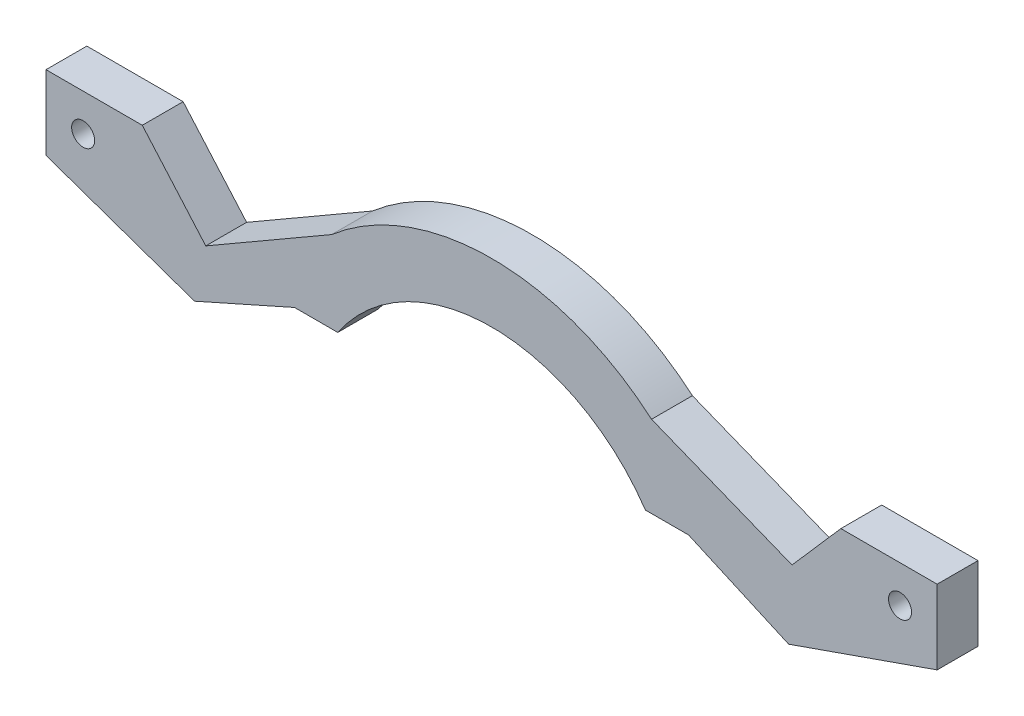
SolidWorks part; units mm, degrees
material "ﾁｰｸ材"
ref_plane "正面" through (0, 0, 0) normal (0, 0, 1) x (1, 0, 0)
ref_plane "平面" through (0, 0, 0) normal (0, 1, 0) x (1, 0, 0)
ref_plane "右側面" through (0, 0, 0) normal (1, 0, 0) x (0, 0, -1)
sketch "ｽｹｯﾁ1" plane through (0, 0, 0) normal (0, 0, 1) x (1, 0, 0)
  line L0 (-60, 5) -> (-47.0333, 5)
  line L2 (60, 5) -> (60, -5)
  line L4 (-60, 5) -> (-60, -5)
  line L5 (60, 5) -> (-60, -5) construction
  line L6 (60, -5) -> (-60, 5) construction
  line L7 (-60, -5) -> (-40, -12)
  line L8 (29.5804, -15) -> (47.0333, 5) construction
  line L9 (-29.5804, -15) -> (-47.0333, 5) construction
  line L10 (-40, -12) -> (-26.533, -6)
  line L11 (-47.0333, 5) -> (-38.4858, -4.7949)
  line L12 (-26.533, -6) -> (-20.7123, -6)
  line L13 (-38.4858, -4.7949) -> (-21.5407, 5)
  line L14 (21.5407, 5) -> (40.4583, -2.5345)
  line L15 (40.4583, -2.5345) -> (47.0333, 5)
  line L16 (60, -5) -> (40, -12)
  line L17 (20.7123, -6) -> (26.533, -6)
  line L18 (26.533, -6) -> (40, -12)
  line L19 (47.0333, 5) -> (60, 5)
  circle A0 centre (0, -20) radius 30 construction
  arc A1 (20.7123, -6) -> (-20.7123, -6) centre (0, -20) ccw
  arc A3 (-21.5407, 5) -> (21.5407, 5) centre (0, -20) cw
  point P0 (0, 0)
  point P12 (-42.7304, 0.0691)
  point P15 (0, 0)
  point P17 (-24.0049, 2.6443)
  point P19 (-21.5506, 0.8703)
  point P24 (-23.832, 3.2073)
  point P25 (-40.3836, -2.6202)
  point P26 (-26.65, -6.224)
  point P29 (-27.9113, -2.3943)
  point P30 (-27.9159, -2.3263)
  point P31 (-27.8656, -2.3221)
  point P32 (-22.9304, 3.7318)
  point P33 (-40.6437, -7.9727)
  point P34 (22.9304, 3.1838)
  point P35 (-23.4633, 3.205)
  dimension "D3" = 60
  dimension "D10" = 50
  dimension "D11" = 20
  dimension "D9" = 33
  dimension "D1" = 10
  dimension "D2" = 120
  dimension "D4" = 25
  dimension "D5" = 5
  dimension "D6" = 5
  dimension "D7" = 19
  dimension "D8" = 19
  dimension "D12" = 7
  dimension "D13" = 13
  dimension "D14" = 20
  dimension "D15" = 14
  dimension "D16" = 10
extrude "ﾎﾞｽ - 押し出し1" add sketch "ｽｹｯﾁ1" along normal blind 5.5
sketch "ｽｹｯﾁ2" plane through (0, 0, 5.5) normal (0, 0, 1) x (1, 0, 0)
  line L0 (-60, 5) -> (-60, -5) construction
  line L1 (60, -5) -> (60, 5) construction
  circle A0 centre (-55, 0) radius 1.55
  circle A1 centre (55, 0) radius 1.55
  dimension "D1" = 3.1
  dimension "D2" = 5
  dimension "D3" = 5
extrude "ｶｯﾄ - 押し出し1" cut sketch "ｽｹｯﾁ2" against normal through all
